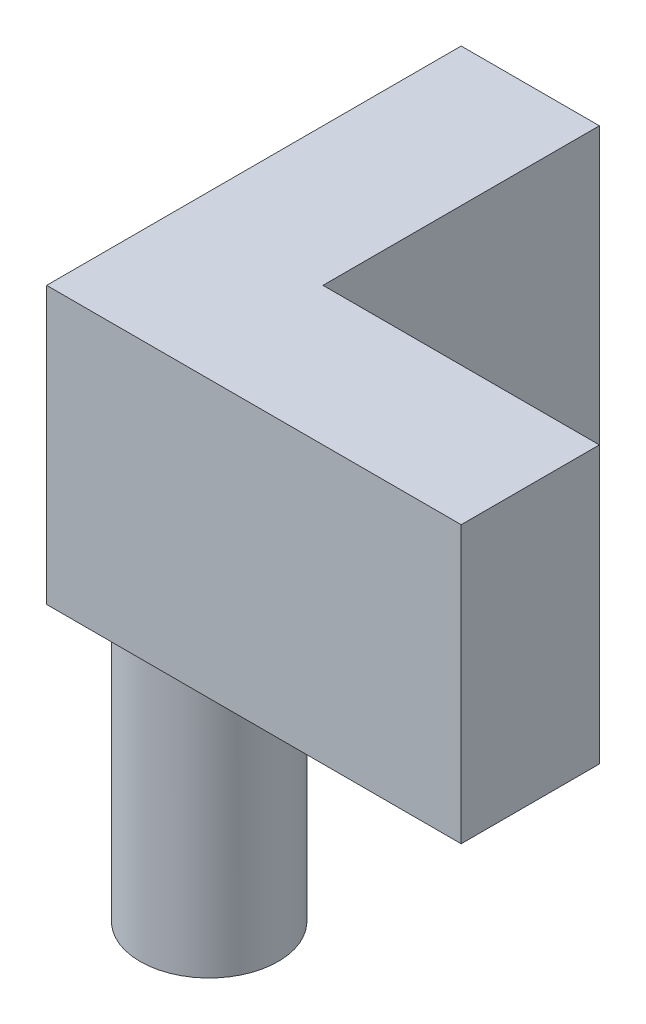
SolidWorks part; units mm, degrees
ref_plane "Front Plane" through (0, 0, 0) normal (0, 0, 1) x (1, 0, 0)
ref_plane "Top Plane" through (0, 0, 0) normal (0, 1, 0) x (1, 0, 0)
ref_plane "Right Plane" through (0, 0, 0) normal (1, 0, 0) x (0, 0, -1)
sketch "Sketch1" plane through (0, 0, 0) normal (0, 1, 0) x (1, 0, 0)
  line L0 (0, 15) -> (0, 0)
  line L3 (0, 15) -> (5, 15)
  line L4 (5, 5) -> (5, 15)
  line L7 (5, 5) -> (15, 5)
  line L8 (15, 0) -> (15, 5)
  line L9 (0, 0) -> (15, 0)
  circle A0 centre (2.8799, 3.0008) radius 2.5
  dimension "D4" = 5
  dimension "D1" = 15
  dimension "D2" = 15
  dimension "D3" = 5
extrude "Boss-Extrude1" add sketch "Sketch1" along normal blind 10
sketch "Sketch2" plane through (0, 10, 0) normal (0, 1, 0) x (1, 0, 0)
  circle A0 centre (2.8799, 3.0008) radius 2.5
extrude "Boss-Extrude2" add sketch "Sketch2" against normal blind 20
